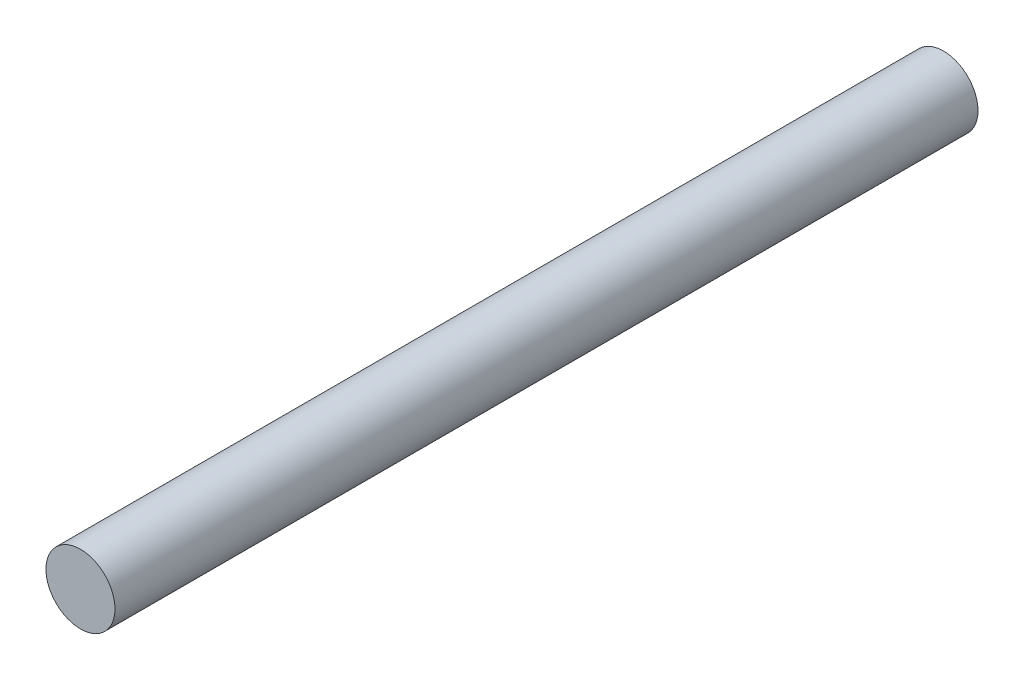
SolidWorks part; units mm, degrees
ref_plane "xy" through (0, 0, 0) normal (0, 0, 1) x (1, 0, 0)
ref_plane "xz" through (0, 0, 0) normal (0, 1, 0) x (1, 0, 0)
ref_plane "yz" through (0, 0, 0) normal (1, 0, 0) x (0, 0, -1)
sketch "Skizze1" plane through (0, 0, 0) normal (0, 0, 1) x (1, 0, 0)
  circle A0 centre (0, 0) radius 4
  dimension "D1" = 8
extrude "Aufsatz-Linear austragen1" add sketch "Skizze1" along normal mid plane 100
cosmetic thread "Gewindedarstellung1" parameters "D2"=6.891
